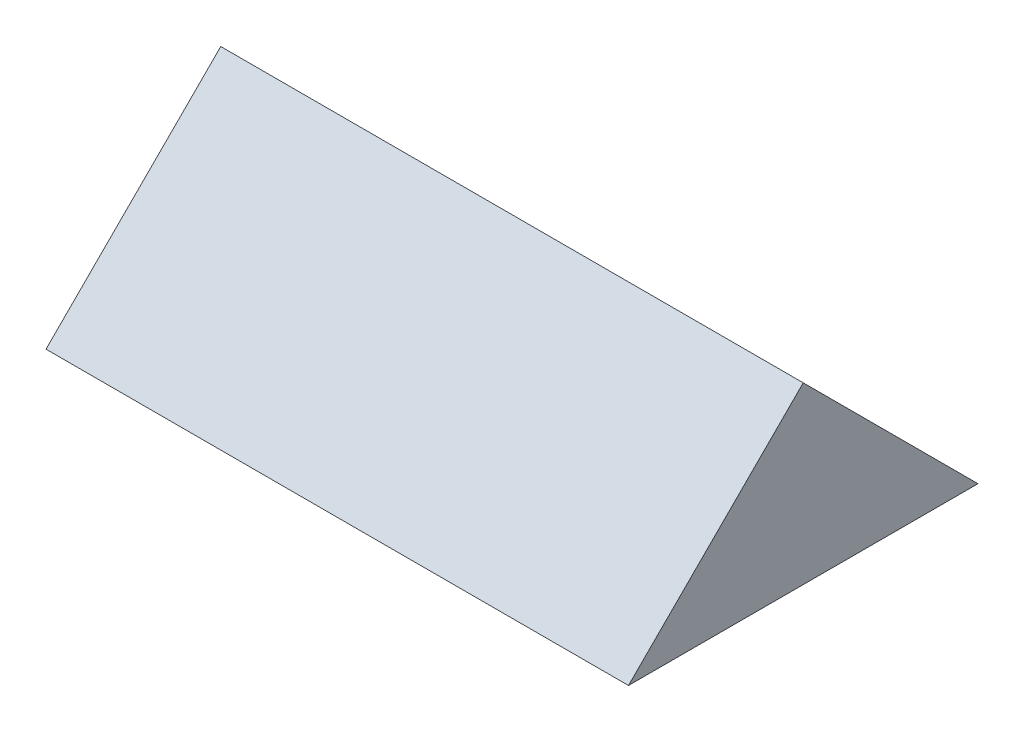
SolidWorks part; units mm, degrees
ref_plane "Front Plane" through (0, 0, 0) normal (0, 0, 1) x (1, 0, 0)
ref_plane "Top Plane" through (0, 0, 0) normal (0, 1, 0) x (1, 0, 0)
ref_plane "Right Plane" through (0, 0, 0) normal (1, 0, 0) x (0, 0, -1)
sketch "Sketch1" plane through (0, 0, 0) normal (1, 0, 0) x (0, 0, -1)
  line L0 (0, 0) -> (7315.2, 0)
  line L1 (7315.2, 0) -> (3657.6, 3657.6)
  line L2 (3657.6, 3657.6) -> (0, 0)
  dimension "D1" = 7315.2
extrude "Boss-Extrude1" add sketch "Sketch1" along normal blind 12192
shell "Shell1" thickness 304.8
